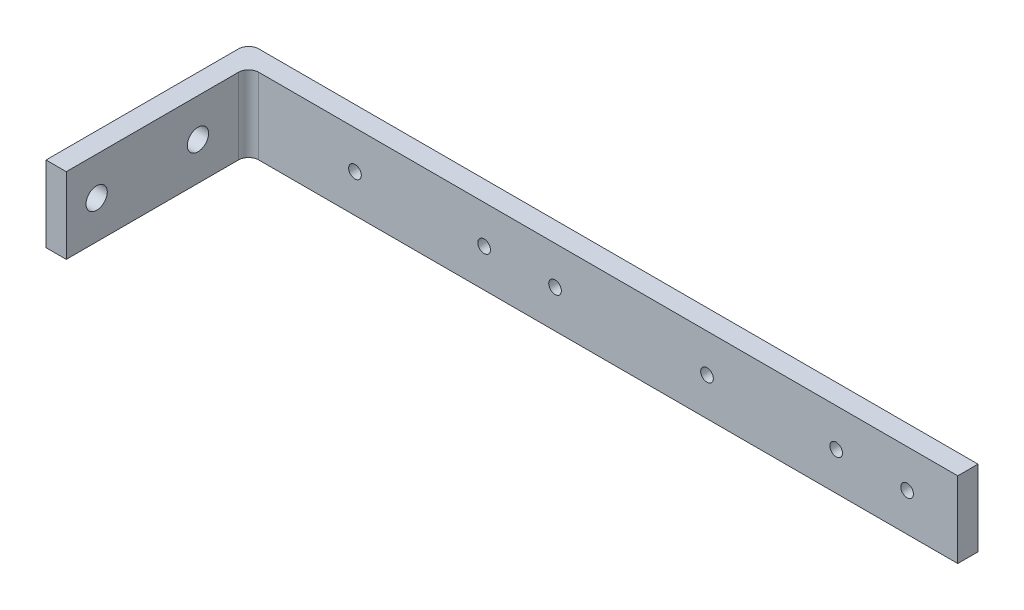
SolidWorks part; units mm, degrees
ref_plane "Front Plane" through (0, 0, 0) normal (0, 0, 1) x (1, 0, 0)
ref_plane "Top Plane" through (0, 0, 0) normal (0, 1, 0) x (1, 0, 0)
ref_plane "Right Plane" through (0, 0, 0) normal (1, 0, 0) x (0, 0, -1)
sketch "Sketch1" plane through (0, 0, 0) normal (0, 0, 1) x (1, 0, 0)
  line L0 (0, 7.5) -> (140, 7.5) construction
  line L1 (0, 0) -> (140, 0)
  line L2 (0, 0) -> (0, 15)
  line L3 (0, 15) -> (140, 15)
  line L4 (140, 0) -> (140, 15)
  point P7 (21, 7.5)
  point P8 (60.5, 7.5)
  point P9 (46.5, 7.5)
  point P10 (90.5, 7.5)
  point P11 (116, 7.5)
  point P12 (130, 7.5)
  dimension "D1" = 15
  dimension "D2" = 140
  dimension "D3" = 39.5
  dimension "D4" = 25.5
  dimension "D5" = 39.5
  dimension "D6" = 25.5
  dimension "D7" = 30
  dimension "D8" = 10
extrude "Boss-Extrude1" add sketch "Sketch1" along normal blind 4
hole_wizard "M3x0.5 Tapped Hole1" positions "Sketch2" profile "Sketch3" tap size "M3x0.5" standard "ANSI Metric" end condition through all
sketch "Sketch2" plane through (0, 0, 0) normal (0, 0, -1) x (-1, 0, 0)
  point P0 (-130, 7.5)
  point P3 (-116, 7.5)
  point P6 (-90.5, 7.5)
  point P9 (-60.5, 7.5)
  point P12 (-46.5, 7.5)
  point P15 (-21, 7.5)
sketch "Sketch3" plane through (130, 7.5, 0) normal (1, 0, 0) x (0, 1, 0)
  line L0 (0, 0) -> (0, 4)
  line L1 (0, 4) -> (1.25, 4)
  line L2 (1.25, 4) -> (1.25, 0)
  line L5 (1.25, 0) -> (0, 0)
  line L11 (0, -6.35) -> (0, 107.95) construction
  dimension "Thru Tap Drill Dia." = 2.5
  dimension "Thru Tap Drill Depth" = 4
cosmetic thread "Hole Thread1" parameters "D2"=3
cosmetic thread "Hole Thread2" parameters "D2"=3
cosmetic thread "Hole Thread3" parameters "D2"=3
cosmetic thread "Hole Thread4" parameters "D2"=3
cosmetic thread "Hole Thread5" parameters "D2"=3
cosmetic thread "Hole Thread6" parameters "D2"=3
sketch "Sketch6" plane through (0, 0, 0) normal (-1, 0, 0) x (0, 0, 1)
  line L1 (0, 0) -> (40, 0)
  line L2 (0, 0) -> (0, 15)
  line L3 (0, 15) -> (40, 15)
  line L4 (40, 0) -> (40, 15)
  dimension "D1" = 15
  dimension "D2" = 40
extrude "Boss-Extrude2" add sketch "Sketch6" along normal blind 4
fillet "Fillet1" radius 2 2 edges at (-4, 7.5, 0) (0, 7.5, 4)
hole_wizard "Ø4.0mm Dowel Hole1" positions "Sketch7" profile "Sketch8" hole size "Ø4.0" standard "ANSI Metric" end condition through all
sketch "Sketch7" plane through (-4, 0, 0) normal (-1, 0, 0) x (0, 0, 1)
  line L0 (40, 7.5) -> (0, 7.5) construction
  line L1 (40, 0) -> (40, 15) construction
  point P0 (34, 7.5)
  point P2 (14, 7.5)
  dimension "D1" = 20
  dimension "D2" = 6
sketch "Sketch8" plane through (-4, 7.5, 34) normal (0, 1, 0) x (0, 0, 1)
  line L0 (0, 0) -> (0, 144)
  line L1 (0, 144) -> (2.1, 144)
  line L2 (2.1, 144) -> (2.1, 0)
  line L5 (2.1, 0) -> (0, 0)
  line L11 (0, -6.35) -> (0, 107.95) construction
  dimension "Thru Hole Dia." = 4.2
  dimension "Thru Hole Depth" = 144
